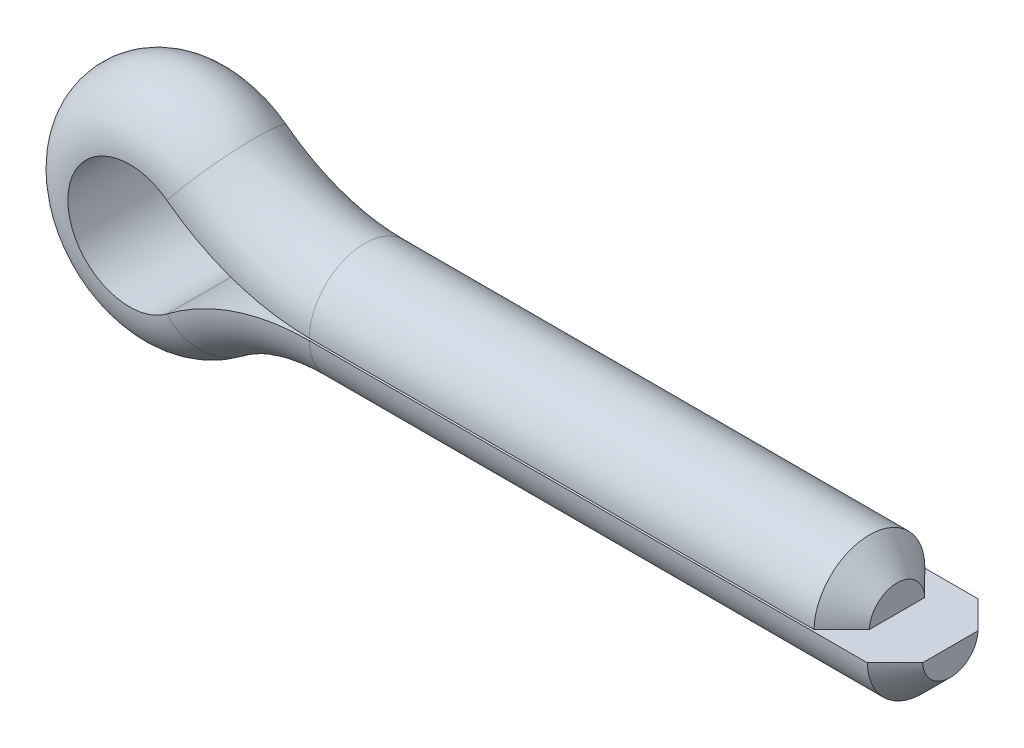
SolidWorks part; units mm, degrees
ref_plane "Front" through (0, 0, 0) normal (0, 0, 1) x (1, 0, 0)
ref_plane "Top" through (0, 0, 0) normal (0, 1, 0) x (1, 0, 0)
ref_plane "Right" through (0, 0, 0) normal (1, 0, 0) x (0, 0, -1)
sketch "Sketch1" plane through (0, 0, 0) normal (0, 0, 1) x (1, 0, 0)
  line L0 (-16.9837, 0) -> (1.27, 0) construction
  line L1 (-12.7, -0.0254) -> (1.27, -0.0254)
  line L2 (-15.5107, 0.0254) -> (1.27, 0.0254) construction
  line L3 (-12.7, 0.0254) -> (0, 0.0254)
  line L4 (-11.4985, 0.0254) -> (1.27, 0.0254) construction
  line L5 (-11.4985, -0.0254) -> (1.27, -0.0254) construction
  line L6 (-16.9837, 1.397) -> (-16.9837, 0) construction
  line L7 (-16.9837, 1.397) -> (-16.9837, 2.794) construction
  line L8 (-11.4985, 0) -> (1.27, 0) construction
  line L9 (0, 0.0254) -> (0, 0) construction
  line L10 (-16.9837, 0) -> (-16.9837, -2.794) construction
  line L11 (-12.7, 1.2954) -> (-12.7, -1.3462) construction
  arc A1 (-16.09, 1.1711) -> (-16.09, -1.1711) centre (-16.9837, 0) ccw
  arc A2 (-12.7, -0.0254) -> (-16.09, -1.1711) centre (-12.7, -5.6134) ccw
  arc A3 (-16.09, 1.1711) -> (-12.7, 0.0254) centre (-12.7, 5.6134) ccw
  circle A4 centre (-16.9837, 0) radius 2.794 construction
  point P15 (0, 0.0254)
  dimension "D6" = 5.588
  dimension "Head Diameter" = 5.588
  dimension "ExtendedProngLength" = 1.27
  dimension "Length" = 12.7
  dimension "Diameter" = 2.6416
  dimension "D1" = 1.3208
  dimension "D4" = 0.0254
  dimension "D5" = 0.0254
sketch "Sketch2" plane through (0, 0, 0) normal (1, 0, 0) x (0, 0, -1)
  line L0 (-1.3206, 0.0254) -> (1.3206, 0.0254)
  line L1 (0, 1.3208) -> (0, -1.3208) construction
  circle A1 centre (0, 0) radius 1.3208 construction
  arc A2 (-1.3206, 0.0254) -> (1.3206, 0.0254) centre (0, 0) cw
  point P5 (0, 0)
  dimension "D1" = 1.3208
sketch "Sketch3" plane through (0, 0, 0) normal (0, 0, 1) x (1, 0, 0)
  line L0 (-12.7, -0.0254) -> (1.27, -0.0254) construction
  line L1 (-12.7, 0.0254) -> (0, 0.0254) construction
  line L2 (-12.7, -0.0254) -> (1.27, -0.0254)
  line L3 (-12.7, 0.0254) -> (0, 0.0254)
  arc A0 (-12.7, -0.0254) -> (-16.09, -1.1711) centre (-12.7, -5.6134) ccw construction
  arc A1 (-16.09, 1.1711) -> (-12.7, 0.0254) centre (-12.7, 5.6134) ccw construction
  arc A2 (-16.09, 1.1711) -> (-16.09, -1.1711) centre (-16.9837, 0) ccw construction
  arc A3 (-12.7, -0.0254) -> (-16.09, -1.1711) centre (-12.7, -5.6134) ccw
  arc A4 (-16.09, 1.1711) -> (-12.7, 0.0254) centre (-12.7, 5.6134) ccw
  arc A5 (-16.09, 1.1711) -> (-16.09, -1.1711) centre (-16.9837, 0) ccw
sketch "Sketch4" plane through (0, 0, 0) normal (1, 0, 0) x (0, 0, -1)
  line L0 (-1.3206, 0.0254) -> (1.3206, 0.0254) construction
  line L1 (-1.3206, 0.0254) -> (1.3206, 0.0254)
  arc A2 (1.3206, 0.0254) -> (-1.3206, 0.0254) centre (0, 0) ccw construction
  arc A3 (1.3206, 0.0254) -> (-1.3206, 0.0254) centre (0, 0) ccw
sweep "Sweep1" add profiles "Sketch4" path "Sketch3"
chamfer "Chamfer1" distance 0.6604 angle 45 2 edges at (1.27, -1.3208, 0) (0, 1.3208, 0)
equation "\"D6@Sketch1\"=\"Head Diameter@Sketch1\""
equation "\"D1@Sketch2\"=\"Diameter@Sketch1\"/2"
equation "\"ExtendedProngLength@Sketch1\" = \"Length@Sketch1\"*.09"
equation "\"D1@Chamfer1\"=\"Diameter@Sketch1\"/4"
equation "\"D1@Sketch1\"=\"Diameter@Sketch1\"/2"
